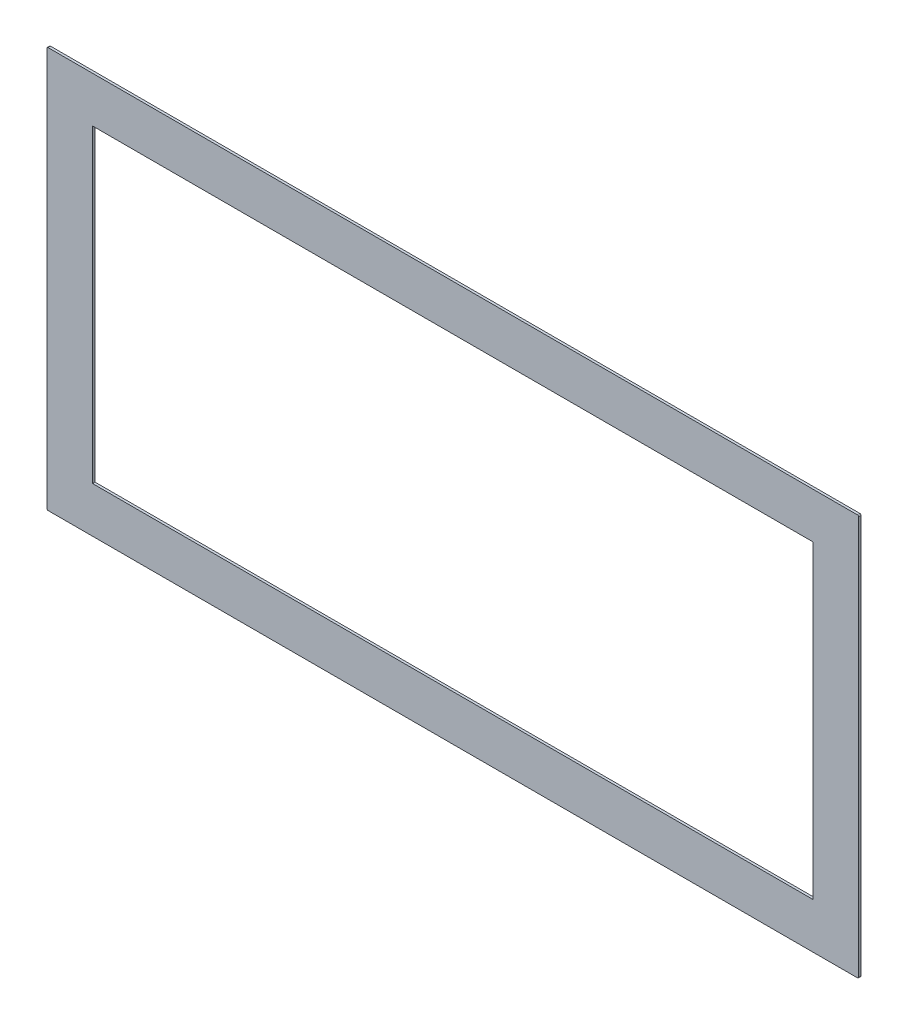
SolidWorks part; units mm, degrees
ref_plane "정면" through (0, 0, 0) normal (0, 0, 1) x (1, 0, 0)
ref_plane "윗면" through (0, 0, 0) normal (0, 1, 0) x (1, 0, 0)
ref_plane "우측면" through (0, 0, 0) normal (1, 0, 0) x (0, 0, -1)
sketch "스케치1" plane through (0, 0, 0) normal (0, 0, 1) x (1, 0, 0)
  line L0 (-328.5, 162.5) -> (-0.5, 162.5)
  line L1 (-329, 162) -> (-329, 0.5)
  line L2 (-328.5, 0) -> (-0.5, 0)
  line L3 (0, 162) -> (0, 0.5)
  line L4 (-310.5, 144) -> (-18.5, 144)
  line L5 (-310.5, 144) -> (-310.5, 18.5)
  line L6 (-310.5, 18.5) -> (-18.5, 18.5)
  line L7 (-18.5, 144) -> (-18.5, 18.5)
  arc A0 (-329, 0.5) -> (-328.5, 0) centre (-328.5, 0.5) ccw
  arc A1 (-0.5, 0) -> (0, 0.5) centre (-0.5, 0.5) ccw
  arc A2 (-0.5, 162.5) -> (0, 162) centre (-0.5, 162) cw
  arc A3 (-328.5, 162.5) -> (-329, 162) centre (-328.5, 162) ccw
  point P8 (0, 0)
  point P12 (-329, 0)
  point P15 (0, 0)
  point P18 (0, 162.5)
  dimension "D7" = 0.5
  dimension "D1" = 18.5
  dimension "D2" = 18.5
  dimension "D3" = 18.5
  dimension "D4" = 18.5
  dimension "D5" = 329
  dimension "D6" = 162.5
extrude "보스-돌출1" add sketch "스케치1" along normal blind 1
